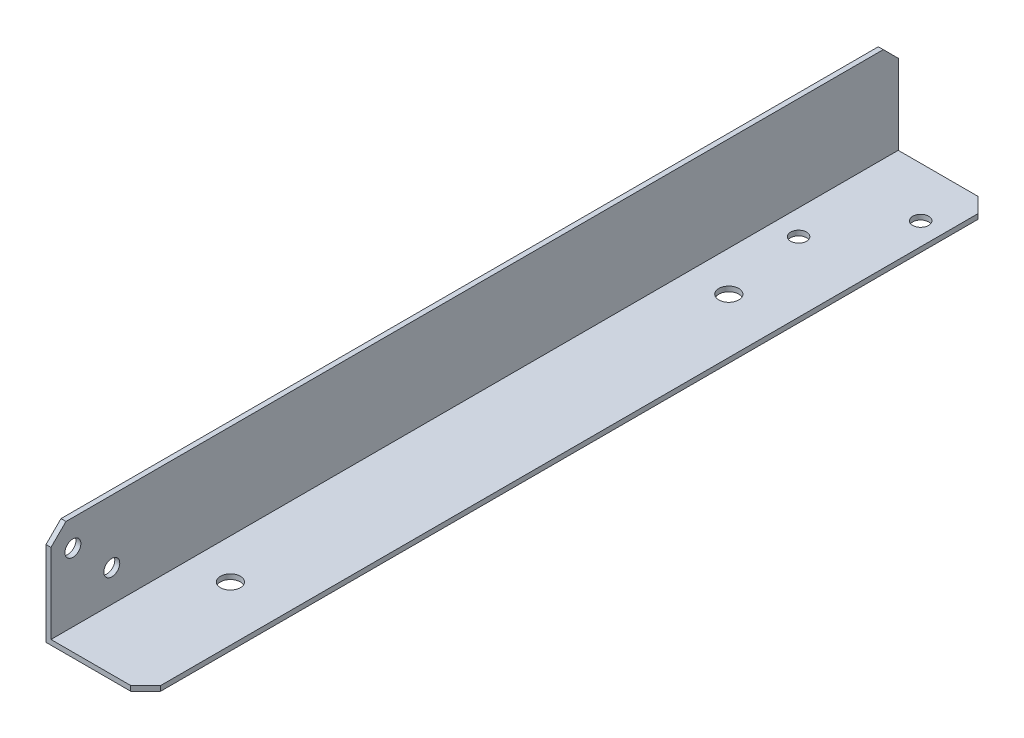
SolidWorks part; units mm, degrees
material "6063-T5"
ref_plane "Спереди" through (0, 0, 0) normal (0, 0, 1) x (1, 0, 0)
ref_plane "Сверху" through (0, 0, 0) normal (0, 1, 0) x (1, 0, 0)
ref_plane "Справа" through (0, 0, 0) normal (1, 0, 0) x (0, 0, -1)
sketch "Sketch1" plane through (0, 0, 0) normal (0, 0, 1) x (1, 0, 0)
  line L0 (0, 0) -> (20, 0)
  line L1 (20, 0) -> (20, 1)
  line L2 (20, 1) -> (1, 1)
  line L3 (1, 1) -> (1, 20)
  line L4 (1, 20) -> (0, 20)
  line L5 (0, 20) -> (0, 0)
  dimension "D1" = 20
  dimension "D2" = 20
  dimension "D3" = 1
  dimension "D4" = 1
extrude "Base" add sketch "Sketch1" along normal blind 170
chamfer "ChamferEdges" distance 3 angle 45 4 edges at (20, 0.5, 170) (0.5, 20, 170) (0.5, 20, 0) (20, 0.5, 0)
hole_wizard "Ø4.0 (4) Cable tie Holes" positions "Sketch8" profile "Sketch9" hole size "Ø4.0" standard "ANSI Metric" end condition through all
sketch "Sketch8" plane through (0, 1, 0) normal (0, 1, 0) x (1, 0, 0)
  line L0 (0, -167) -> (0, -3) construction
  line L1 (17, 0) -> (1, 0) construction
  point P0 (9, -42)
  point P2 (9, -142)
  dimension "D1" = 9
  dimension "D2" = 42
  dimension "D3" = 142
sketch "Sketch9" plane through (9, 1, 42) normal (1, 0, 0) x (0, 0, 1)
  line L0 (0, 0) -> (0, 1)
  line L1 (0, 1) -> (2, 1)
  line L2 (2, 1) -> (2, 0)
  line L5 (2, 0) -> (0, 0)
  line L11 (0, -6.35) -> (0, 107.95) construction
  dimension "Thru Hole Dia." = 4
  dimension "Thru Hole Depth" = 1
hole_wizard "Ø3.1 (3.1) CableChainSideHoles" positions "Sketch10" profile "Sketch11" hole size "Ø3.2" standard "ANSI Metric" end condition through all
sketch "Sketch10" plane through (1, 0, 0) normal (1, 0, 0) x (0, 0, -1)
  line L0 (-167, 0) -> (-3, 0) construction
  line L1 (-170, 1) -> (-170, 17) construction
  point P0 (-165.6, 14.68)
  point P2 (-157.8, 7.38)
  dimension "D1" = 7.3
  dimension "D2" = 7.8
  dimension "D3" = 7.38
  dimension "D4" = 4.4
sketch "Sketch11" plane through (1, 14.68, 165.6) normal (0, 1, 0) x (0, 0, -1)
  line L0 (0, 0) -> (0, 1)
  line L1 (0, 1) -> (1.6, 1)
  line L2 (1.6, 1) -> (1.6, 0)
  line L5 (1.6, 0) -> (0, 0)
  line L11 (0, -6.35) -> (0, 107.95) construction
  dimension "Thru Hole Dia." = 3.2
  dimension "Thru Hole Depth" = 1
hole_wizard "Ø3.2 (3.2) CarriageSide" positions "Sketch12" profile "Sketch13" hole size "Ø3.2" standard "ANSI Metric" end condition through all
sketch "Sketch12" plane through (0, 1, 0) normal (0, 1, 0) x (1, 0, 0)
  line L0 (0, -167) -> (0, -3) construction
  line L1 (17, 0) -> (1, 0) construction
  point P0 (15.5, -10)
  point P2 (6, -25)
  dimension "D1" = 6
  dimension "D2" = 15
  dimension "D3" = 10
  dimension "D4" = 9.5
sketch "Sketch13" plane through (15.5, 1, 10) normal (1, 0, 0) x (0, 0, 1)
  line L0 (0, 0) -> (0, 1)
  line L1 (0, 1) -> (1.6, 1)
  line L2 (1.6, 1) -> (1.6, 0)
  line L5 (1.6, 0) -> (0, 0)
  line L11 (0, -6.35) -> (0, 107.95) construction
  dimension "Thru Hole Dia." = 3.2
  dimension "Thru Hole Depth" = 1
equation "\"D2@Sketch1\"=\"D1@Sketch1\""
equation "\"D4@Sketch1\"=\"D3@Sketch1\""
